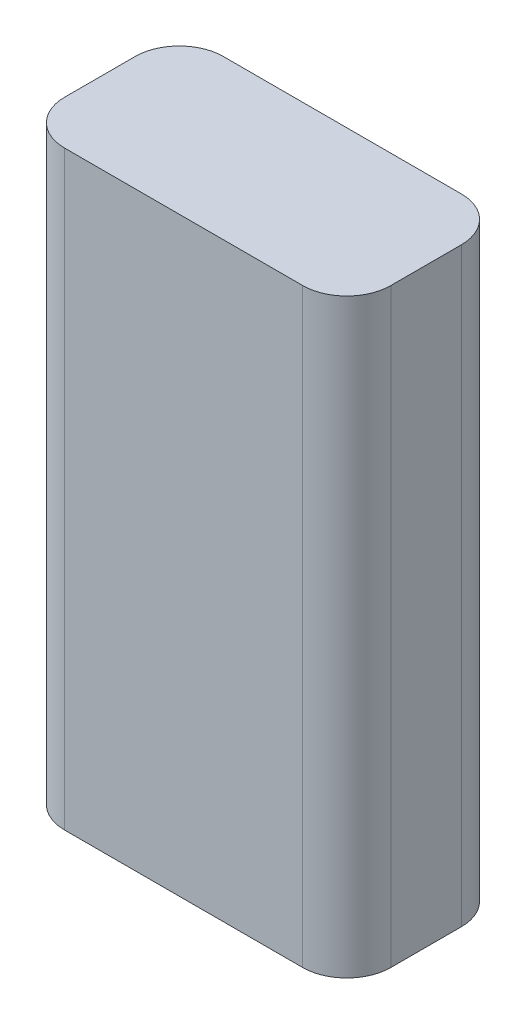
SolidWorks part; units mm, degrees
ref_plane "前视基准面" through (0, 0, 0) normal (0, 0, 1) x (1, 0, 0)
ref_plane "上视基准面" through (0, 0, 0) normal (0, 1, 0) x (1, 0, 0)
ref_plane "右视基准面" through (0, 0, 0) normal (1, 0, 0) x (0, 0, -1)
sketch "草图1" plane through (0, 0, 0) normal (0, 0, 1) x (1, 0, 0)
  line L1 (-18.5, -33.5) -> (18.5, -33.5)
  line L2 (-18.5, -33.5) -> (-18.5, 33.5)
  line L3 (-18.5, 33.5) -> (18.5, 33.5)
  line L4 (18.5, -33.5) -> (18.5, 33.5)
  line L5 (0, 33.5) -> (0, -33.5) construction
  line L6 (-18.5, 0) -> (18.5, 0) construction
  point P0 (0, 0)
  dimension "D1" = 37
  dimension "D2" = 67
extrude "凸台-拉伸1" add sketch "草图1" along normal blind 18
fillet "圆角2" radius 5 4 edges at (18.5, 0, 18) (-18.5, 0, 18) (-18.5, 0, 0) (18.5, 0, 0)
